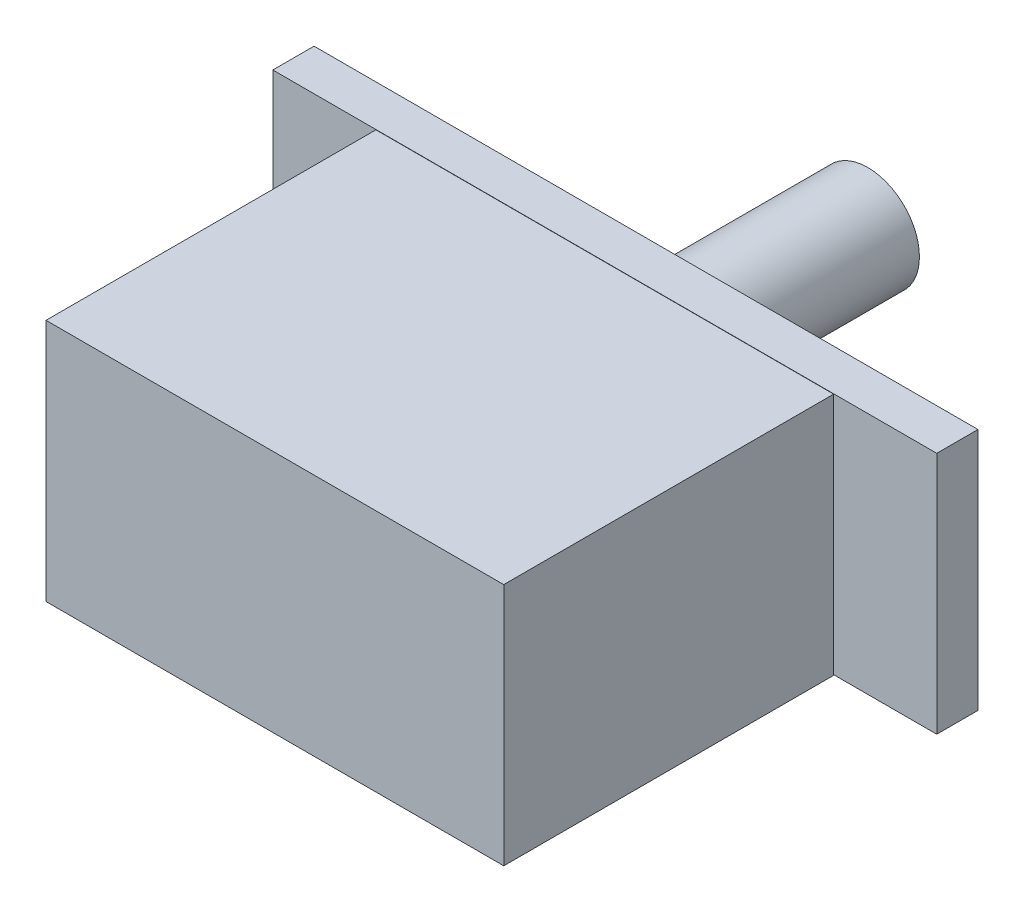
SolidWorks part; units mm, degrees
ref_plane "Plano frontal" through (0, 0, 0) normal (0, 0, 1) x (1, 0, 0)
ref_plane "Plano superior" through (0, 0, 0) normal (0, 1, 0) x (1, 0, 0)
ref_plane "Plano direito" through (0, 0, 0) normal (1, 0, 0) x (0, 0, -1)
sketch "Esboço1" plane through (0, 0, 0) normal (0, 0, 1) x (1, 0, 0)
  line L1 (-65.3547, -7.0775) -> (-33.1547, -7.0775)
  line L2 (-65.3547, -7.0775) -> (-65.3547, -18.8775)
  line L3 (-65.3547, -18.8775) -> (-33.1547, -18.8775)
  line L4 (-33.1547, -7.0775) -> (-33.1547, -18.8775)
extrude "Ressalto-extrusão1" add sketch "Esboço1" along normal blind 2
sketch "Esboço2" plane through (0, 0, 2) normal (0, 0, 1) x (1, 0, 0)
  line L1 (-60.3547, -18.9042) -> (-38.1547, -18.9042)
  line L2 (-60.3547, -18.9042) -> (-60.3547, -7.0916)
  line L3 (-60.3547, -7.0916) -> (-38.1547, -7.0916)
  line L4 (-38.1547, -18.9042) -> (-38.1547, -7.0916)
  line L7 (-65.3547, -7.0775) -> (-65.3547, -18.8775) construction
  line L9 (-33.1547, -18.8775) -> (-33.1547, -7.0775) construction
  dimension "D1" = 5
  dimension "D2" = 5
extrude "Ressalto-extrusão2" add sketch "Esboço2" along normal blind 16
sketch "Esboço3" plane through (0, 0, 0) normal (0, 0, -1) x (-1, 0, 0)
  circle A0 centre (50.496, -13.2453) radius 2.5
  dimension "D1" = 5
extrude "Ressalto-extrusão3" add sketch "Esboço3" along normal blind 12
